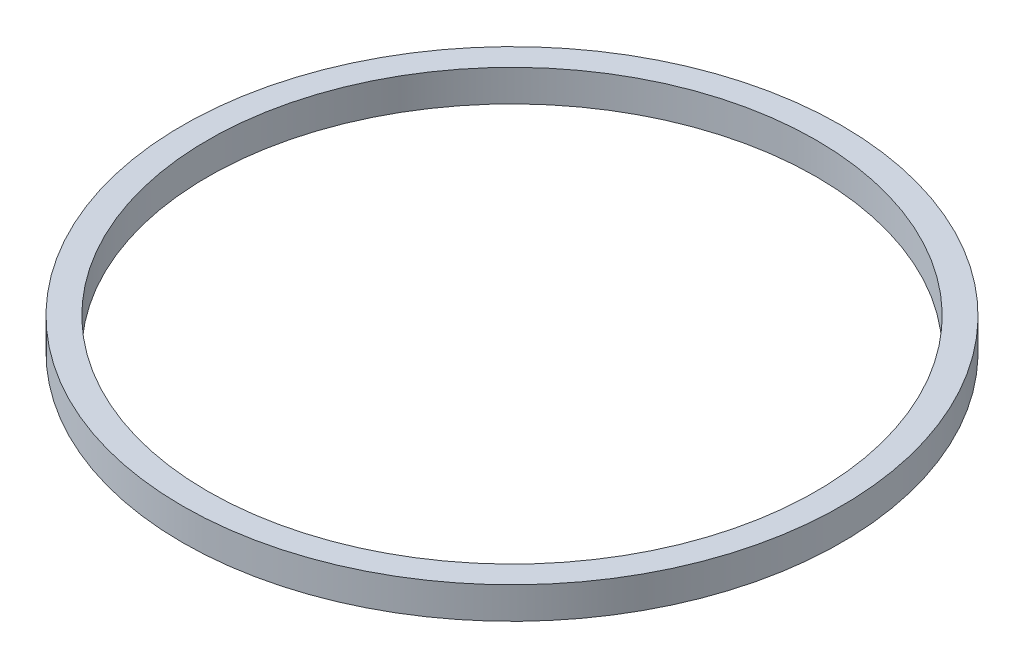
SolidWorks part; units mm, degrees
ref_plane "Front Plane" through (0, 0, 0) normal (0, 0, 1) x (1, 0, 0)
ref_plane "Top Plane" through (0, 0, 0) normal (0, 1, 0) x (1, 0, 0)
ref_plane "Right Plane" through (0, 0, 0) normal (1, 0, 0) x (0, 0, -1)
sketch "Sketch1" plane through (0, 0, 0) normal (0, 1, 0) x (1, 0, 0)
  circle A0 centre (0, 0) radius 24
  circle A1 centre (0, 0) radius 26
  dimension "D1" = 52
  dimension "D2" = 48
extrude "Boss-Extrude1" add sketch "Sketch1" along normal blind 2.5
